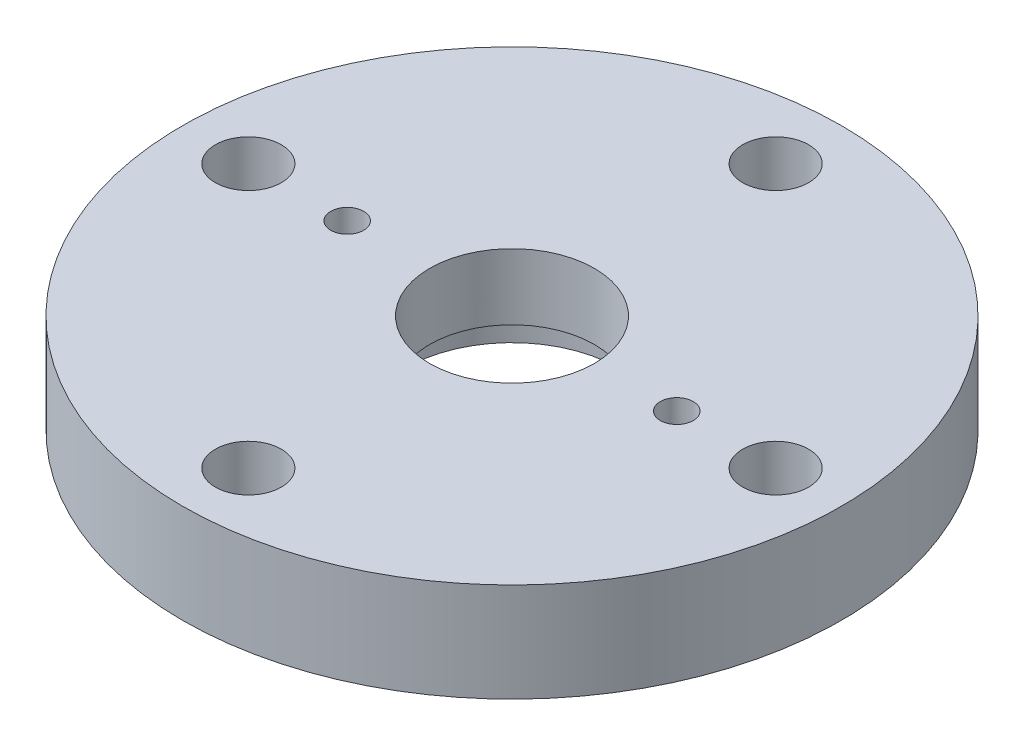
SolidWorks part; units mm, degrees
ref_plane "前视基准面" through (0, 0, 0) normal (0, 0, 1) x (1, 0, 0)
ref_plane "上视基准面" through (0, 0, 0) normal (0, 1, 0) x (1, 0, 0)
ref_plane "右视基准面" through (0, 0, 0) normal (1, 0, 0) x (0, 0, -1)
sketch "草图1" plane through (0, 0, 0) normal (0, 1, 0) x (1, 0, 0)
  circle A0 centre (0, 0) radius 10
  dimension "D1" = 20
extrude "凸台-拉伸1" add sketch "草图1" along normal blind 3
sketch "草图2" plane through (0, 0, 0) normal (0, 1, 0) x (1, 0, 0)
  line L0 (0, 0) -> (14.3174, 0) construction
  line L1 (14.3174, 0) -> (0, 0) construction
  line L2 (0, 0) -> (0, 10.7381) construction
  line L3 (0, 0) -> (9.9629, 9.9629) construction
  circle A0 centre (8, 0) radius 1
  circle A1 centre (5, 0) radius 0.5
  circle A2 centre (-5, 0) radius 0.5
  circle A3 centre (-8, 0) radius 1
  circle A4 centre (0, 8) radius 1
  circle A5 centre (0, -8) radius 1
  point P9 (9.9828, 0)
  point P10 (9, 0)
  dimension "D1" = 2
  dimension "D2" = 1
  dimension "D3" = 5
  dimension "D4" = 8
  dimension "D5" = 45
extrude "切除-拉伸1" cut sketch "草图2" along normal blind 3
sketch "草图4" plane through (0, 0, 0) normal (0, 1, 0) x (1, 0, 0)
  circle A0 centre (0, 0) radius 3.25
  dimension "D1" = 6.5
extrude "切除-拉伸5" cut sketch "草图4" along normal blind 1
sketch "草图5" plane through (0, 1, 0) normal (0, -1, 0) x (1, 0, 0)
  circle A0 centre (0, 0) radius 2.5
  dimension "D1" = 5
extrude "切除-拉伸6" cut sketch "草图5" against normal up to next
